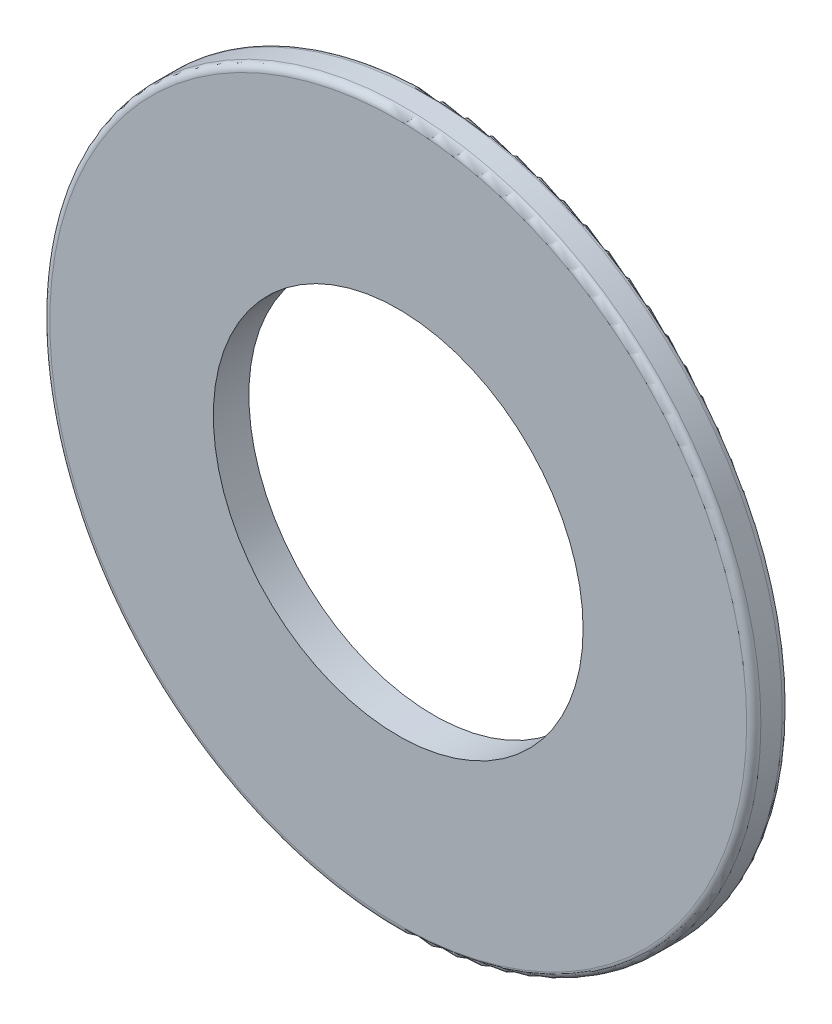
SolidWorks part; units mm, degrees
ref_plane "前视基准面" through (0, 0, 0) normal (0, 0, 1) x (1, 0, 0)
ref_plane "上视基准面" through (0, 0, 0) normal (0, 1, 0) x (1, 0, 0)
ref_plane "右视基准面" through (0, 0, 0) normal (1, 0, 0) x (0, 0, -1)
other "Configuration Table"
sketch "草图1" plane through (0, 0, 0) normal (0, 0, 1) x (1, 0, 0)
  circle A0 centre (0, 0) radius 5
  circle A1 centre (0, 0) radius 2.6
  dimension "D1" = 10
  dimension "D2" = 5.2
extrude "凸台-拉伸1" add sketch "草图1" along normal blind 0.5
fillet "圆角1" radius 0.1 2 edges at (5, 0, 0) (5, 0, 0.5)
